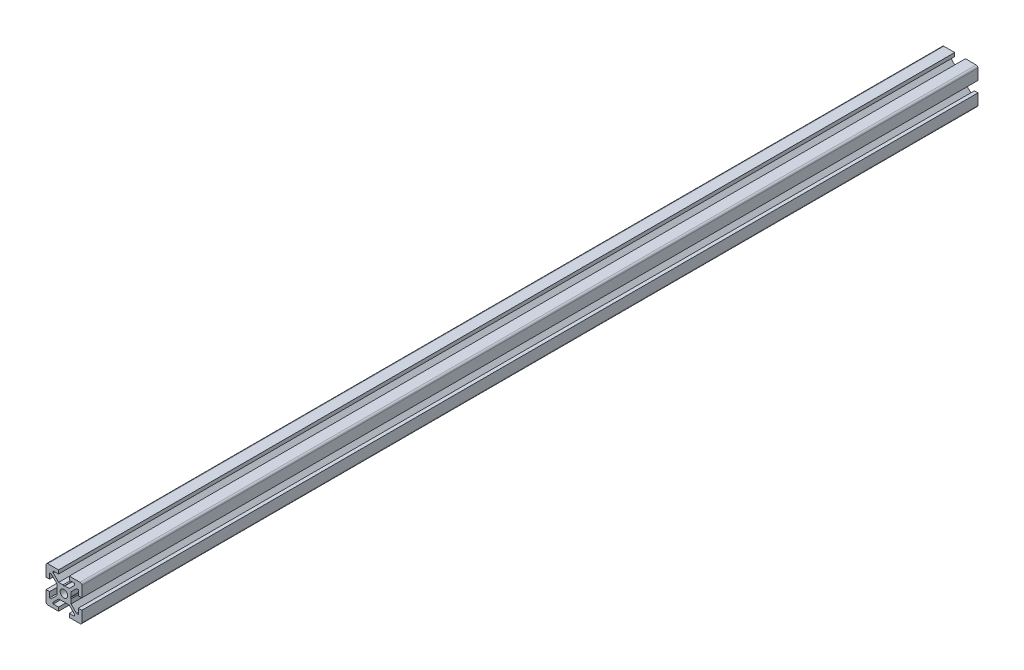
SolidWorks part; units mm, degrees
ref_plane "Front Plane" through (0, 0, 0) normal (0, 0, 1) x (1, 0, 0)
ref_plane "Top Plane" through (0, 0, 0) normal (0, 1, 0) x (1, 0, 0)
ref_plane "Right Plane" through (0, 0, 0) normal (1, 0, 0) x (0, 0, -1)
ref_plane "Plane1" through (0, 0, -500) normal (0, 0, -1) x (-1, 0, 0)
sketch "Sketch1" plane through (0, 0, -500) normal (0, 0, -1) x (-1, 0, 0)
  line L0 (9, 10) -> (3, 10)
  line L1 (3, 10) -> (3, 8)
  line L2 (3, 8) -> (6, 8)
  line L3 (6, 8) -> (6, 7.0607)
  line L4 (6, 7.0607) -> (2.9393, 4)
  line L5 (2.9393, 4) -> (0.5196, 4)
  line L6 (0.5196, 4) -> (0, 3.7)
  line L7 (0, 3.7) -> (-0.5196, 4)
  line L8 (-0.5196, 4) -> (-2.9393, 4)
  line L9 (-2.9393, 4) -> (-6, 7.0607)
  line L10 (-6, 7.0607) -> (-6, 8)
  line L11 (-6, 8) -> (-3, 8)
  line L12 (-3, 8) -> (-3, 10)
  line L13 (-3, 10) -> (-9, 10)
  line L14 (-10, 9) -> (-10, 3)
  line L15 (-10, 3) -> (-8, 3)
  line L16 (-8, 3) -> (-8, 6)
  line L17 (-8, 6) -> (-7.0607, 6)
  line L18 (-7.0607, 6) -> (-4, 2.9393)
  line L19 (-4, 2.9393) -> (-4, 0.5196)
  line L20 (-4, 0.5196) -> (-3.7, 0)
  line L21 (-3.7, 0) -> (-4, -0.5196)
  line L22 (-4, -0.5196) -> (-4, -2.9393)
  line L23 (-4, -2.9393) -> (-7.0607, -6)
  line L24 (-7.0607, -6) -> (-8, -6)
  line L25 (-8, -6) -> (-8, -3)
  line L26 (-8, -3) -> (-10, -3)
  line L27 (-10, -3) -> (-10, -9)
  line L28 (-9, -10) -> (-3, -10)
  line L29 (-3, -10) -> (-3, -8)
  line L30 (-3, -8) -> (-6, -8)
  line L31 (-6, -8) -> (-6, -7.0607)
  line L32 (-6, -7.0607) -> (-2.9393, -4)
  line L33 (-2.9393, -4) -> (-0.5196, -4)
  line L34 (-0.5196, -4) -> (0, -3.7)
  line L35 (0, -3.7) -> (0.5196, -4)
  line L36 (0.5196, -4) -> (2.9393, -4)
  line L37 (2.9393, -4) -> (6, -7.0607)
  line L38 (6, -7.0607) -> (6, -8)
  line L39 (6, -8) -> (3, -8)
  line L40 (3, -8) -> (3, -10)
  line L41 (3, -10) -> (9, -10)
  line L42 (10, -9) -> (10, -3)
  line L43 (10, -3) -> (8, -3)
  line L44 (8, -3) -> (8, -6)
  line L45 (8, -6) -> (7.0607, -6)
  line L46 (7.0607, -6) -> (4, -2.9393)
  line L47 (4, -2.9393) -> (4, -0.5196)
  line L48 (4, -0.5196) -> (3.7, 0)
  line L49 (3.7, 0) -> (4, 0.5196)
  line L50 (4, 0.5196) -> (4, 2.9393)
  line L51 (4, 2.9393) -> (7.0607, 6)
  line L52 (7.0607, 6) -> (8, 6)
  line L53 (8, 6) -> (8, 3)
  line L54 (8, 3) -> (10, 3)
  line L55 (10, 3) -> (10, 9)
  circle A0 centre (0, 0) radius 2.1
  arc A1 (10, 9) -> (9, 10) centre (9, 9) ccw
  arc A2 (-9, 10) -> (-10, 9) centre (-9, 9) ccw
  arc A3 (-10, -9) -> (-9, -10) centre (-9, -9) ccw
  arc A4 (9, -10) -> (10, -9) centre (9, -9) ccw
extrude "Boss-Extrude1" add sketch "Sketch1" against normal blind 500
